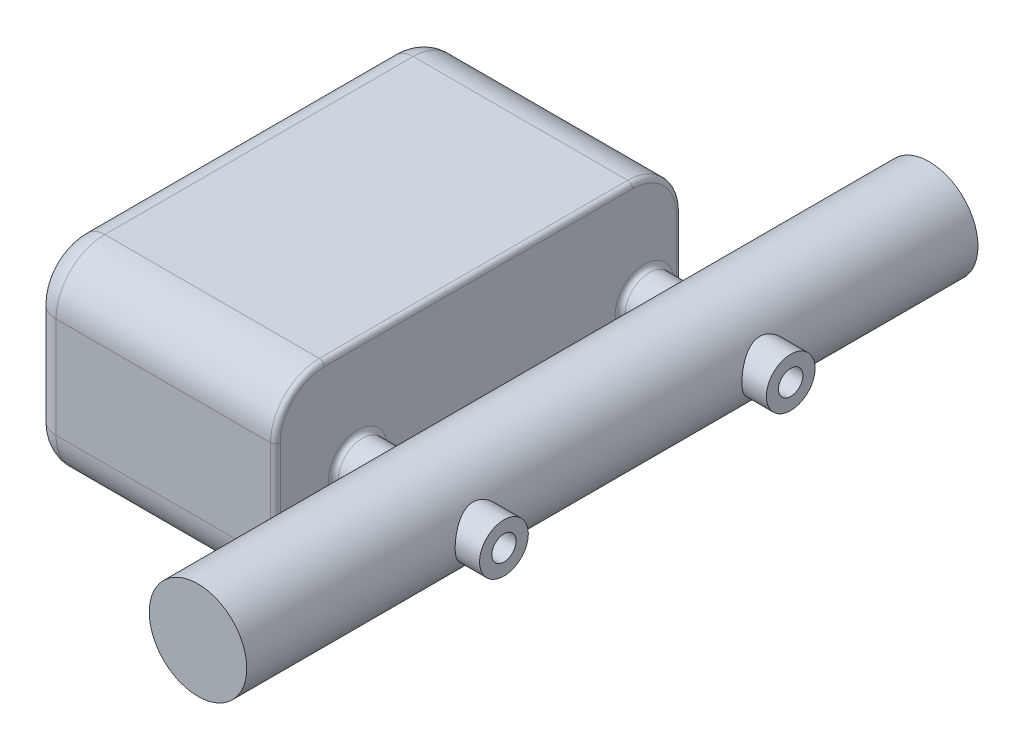
SolidWorks part; units mm, degrees
ref_plane "Płaszczyzna przednia" through (0, 0, 0) normal (0, 0, 1) x (1, 0, 0)
ref_plane "Płaszczyzna górna" through (0, 0, 0) normal (0, 1, 0) x (1, 0, 0)
ref_plane "Płaszczyzna prawa" through (0, 0, 0) normal (1, 0, 0) x (0, 0, -1)
sketch "Szkic1" plane through (0, 0, 0) normal (0, 0, 1) x (1, 0, 0)
  circle A0 centre (0, 0) radius 20
  dimension "D1" = 40
extrude "Dodanie-wyciągnięcie1" add sketch "Szkic1" along normal blind 300
sketch "Szkic2" plane through (0, 0, 0) normal (1, 0, 0) x (0, 0, -1)
  circle A0 centre (-86.8399, 0) radius 5
  circle A1 centre (-204.4816, 0) radius 5
  circle A2 centre (-204.4816, 0) radius 10
  circle A3 centre (-86.8399, 0) radius 10
  dimension "D1" = 10
  dimension "D2" = 20
  dimension "D3" = 10
  dimension "D4" = 20
extrude "Dodanie-wyciągnięcie2" add sketch "Szkic2" along normal blind 30
mirror "Lustro1" about plane through (0, 0, 0) normal (1, 0, 0) of "Dodanie-wyciągnięcie2"
sketch "Szkic3" plane through (-30, 0, 0) normal (-1, 0, 0) x (0, 0, 1)
  line L1 (91.7329, -38.0889) -> (218.2312, -38.0889)
  line L2 (71.7329, -18.0889) -> (71.7329, 23.2317)
  line L3 (91.7329, 43.2317) -> (218.2312, 43.2317)
  line L4 (238.2312, -18.0889) -> (238.2312, 23.2317)
  arc A0 (91.7329, -38.0889) -> (71.7329, -18.0889) centre (91.7329, -18.0889) cw
  arc A1 (218.2312, -38.0889) -> (238.2312, -18.0889) centre (218.2312, -18.0889) ccw
  arc A2 (218.2312, 43.2317) -> (238.2312, 23.2317) centre (218.2312, 23.2317) cw
  arc A3 (71.7329, 23.2317) -> (91.7329, 43.2317) centre (91.7329, 23.2317) cw
  dimension "D1" = 20
extrude "Dodanie-wyciągnięcie3" add sketch "Szkic3" along normal blind 100
fillet "Zaokrąglenie1" radius 10 8 edges at (-130, 2.5714, 71.7329) (-130, 37.3738, 77.5908) (-130, 43.2317, 154.9821) (-130, 37.3738, 232.3734) (-130, 2.5714, 238.2312) (-130, -32.231, 232.3734) (-130, -38.0889, 154.9821) (-130, -32.231, 77.5908)
fillet "Zaokrąglenie2" radius 2 10 edges at (-30, -38.0889, 154.9821) (-30, -32.231, 232.3734) (-30, 2.5714, 238.2312) (-30, 37.3738, 232.3734) (-30, 43.2317, 154.9821) (-30, 37.3738, 77.5908) (-30, 2.5714, 71.7329) (-30, -32.231, 77.5908) (-30, 0, 76.8399) (-30, 0, 194.4816)
